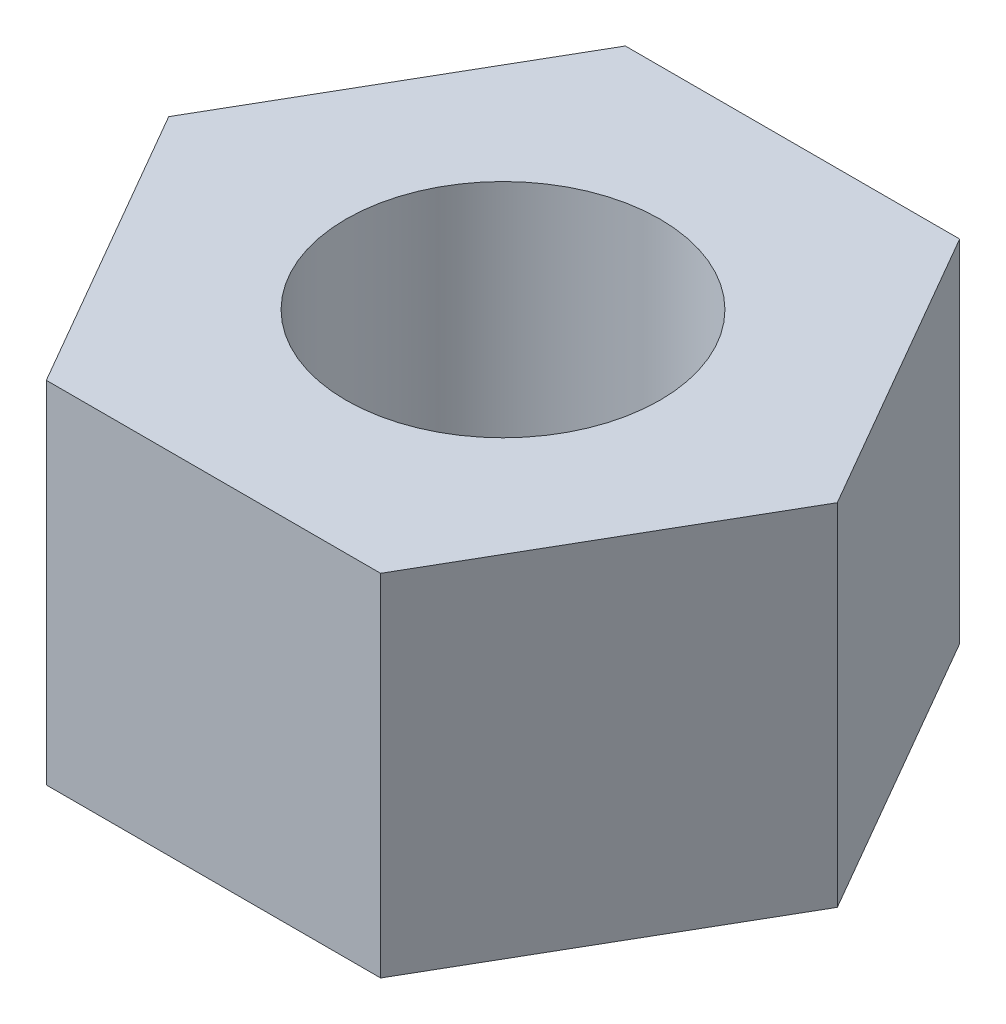
SolidWorks part; units mm, degrees
ref_plane "Front Plane" through (0, 0, 0) normal (0, 0, 1) x (1, 0, 0)
ref_plane "Top Plane" through (0, 0, 0) normal (0, 1, 0) x (1, 0, 0)
ref_plane "Right Plane" through (0, 0, 0) normal (1, 0, 0) x (0, 0, -1)
sketch "Sketch1" plane through (0, 0, 0) normal (0, 1, 0) x (1, 0, 0)
  line L0 (10.9697, 0) -> (0, 0) construction
  line L1 (10.9697, 0) -> (5.4848, 9.5)
  line L2 (5.4848, 9.5) -> (-5.4848, 9.5)
  line L3 (-5.4848, 9.5) -> (-10.9697, 0)
  line L4 (-10.9697, 0) -> (-5.4848, -9.5)
  line L5 (-5.4848, -9.5) -> (5.4848, -9.5)
  line L6 (5.4848, -9.5) -> (10.9697, 0)
  circle A0 centre (0, 0) radius 5.15
  circle A1 centre (0, 0) radius 9.5 construction
  dimension "D1" = 19
  dimension "D2" = 10.3
extrude "Boss-Extrude1" add sketch "Sketch1" along normal blind 11.5
